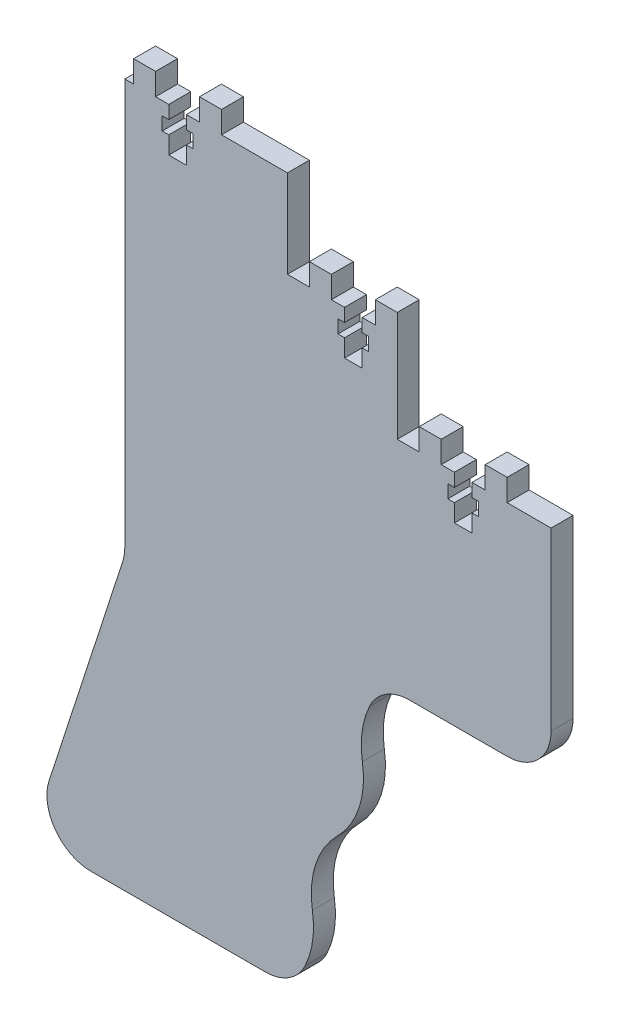
SolidWorks part; units mm, degrees
ref_plane "Plan de face" through (0, 0, 0) normal (0, 0, 1) x (1, 0, 0)
ref_plane "Plan de dessus" through (0, 0, 0) normal (0, 1, 0) x (1, 0, 0)
ref_plane "Plan de droite" through (0, 0, 0) normal (1, 0, 0) x (0, 0, -1)
sketch "Esquisse1" plane through (0, 0, 0) normal (0, 0, 1) x (1, 0, 0)
  line L0 (10, 0) -> (10, -20)
  line L1 (10, -20) -> (15, -20)
  line L2 (35, -20) -> (45, -20)
  line L3 (45, -20) -> (45, -70)
  line L4 (45, -70) -> (7.7444, -70)
  line L5 (7.7444, -70) -> (-15, -140) construction
  line L6 (-15, -140) -> (-73.4888, -140)
  line L7 (-73.4888, -140) -> (-28, 0) construction
  line L8 (-28, 0) -> (-10, 0) construction
  line L9 (-10, 0) -> (-15, 0)
  line L10 (-30, 20) -> (-15, 20)
  line L11 (-50, 20) -> (-52, 20)
  line L12 (-52, 20) -> (-52, -73.8644)
  line L13 (-52, -73.8644) -> (-73.4888, -140)
  line L14 (-15, 20) -> (-15, 0)
  arc A0 (7.7444, -70) -> (2.0583, -87.5) centre (22.0162, -84.311) ccw
  arc A1 (2.0583, -87.5) -> (-3.6278, -105) centre (-17.8996, -90.689) cw
  arc A2 (-3.6278, -105) -> (-9.3139, -122.5) centre (10.644, -119.311) ccw
  arc A3 (-9.3139, -122.5) -> (-15, -140) centre (-29.2718, -125.689) cw
  line B0 (28.5, -23) -> (28.5, -26)
  line B1 (23, -26) -> (23, -30)
  line B2 (27, -30) -> (27, -26)
  line B3 (28.5, -26) -> (27, -26)
  line B4 (25, -20) -> (25, -31.2208) construction
  line B5 (27, -20) -> (30, -20)
  line B6 (30, -15) -> (35, -15)
  line B7 (35, -15) -> (35, -20)
  line B8 (30, -15) -> (30, -20)
  line B9 (23, -20) -> (20, -20)
  line B10 (20, -20) -> (20, -15)
  line B11 (20, -15) -> (15, -15)
  line B12 (15, -15) -> (15, -20)
  line B13 (27, -20) -> (23, -20) construction
  line B14 (23, -20) -> (23, -23)
  line B15 (23, -26) -> (21.5, -26)
  line B16 (21.5, -23) -> (23, -23)
  line B17 (23, -30) -> (27, -30)
  line B18 (27, -23) -> (28.5, -23)
  line B19 (21.5, -26) -> (21.5, -23)
  line B20 (27, -23) -> (27, -20)
  line B21 (25, -30) -> (25, -20) construction
  line B22 (3.5, -3) -> (3.5, -6)
  line B23 (-2, -6) -> (-2, -10)
  line B24 (2, -10) -> (2, -6)
  line B25 (3.5, -6) -> (2, -6)
  line B26 (0, 0) -> (0, -11.2208) construction
  line B27 (2, 0) -> (5, 0)
  line B28 (5, 5) -> (10, 5)
  line B29 (10, 5) -> (10, 0)
  line B30 (5, 5) -> (5, 0)
  line B31 (-2, 0) -> (-5, 0)
  line B32 (-5, 0) -> (-5, 5)
  line B33 (-5, 5) -> (-10, 5)
  line B34 (-10, 5) -> (-10, 0)
  line B35 (2, 0) -> (-2, 0) construction
  line B36 (-2, 0) -> (-2, -3)
  line B37 (-2, -6) -> (-3.5, -6)
  line B38 (-3.5, -3) -> (-2, -3)
  line B39 (-2, -10) -> (2, -10)
  line B40 (2, -3) -> (3.5, -3)
  line B41 (-3.5, -6) -> (-3.5, -3)
  line B42 (2, -3) -> (2, 0)
  line B43 (0, -10) -> (0, 0) construction
  line B44 (-36.5, 17) -> (-36.5, 14)
  line B45 (-42, 14) -> (-42, 10)
  line B46 (-38, 10) -> (-38, 14)
  line B47 (-36.5, 14) -> (-38, 14)
  line B48 (-40, 20) -> (-40, 8.7792) construction
  line B49 (-38, 20) -> (-35, 20)
  line B50 (-35, 25) -> (-30, 25)
  line B51 (-30, 25) -> (-30, 20)
  line B52 (-35, 25) -> (-35, 20)
  line B53 (-42, 20) -> (-45, 20)
  line B54 (-45, 20) -> (-45, 25)
  line B55 (-45, 25) -> (-50, 25)
  line B56 (-50, 25) -> (-50, 20)
  line B57 (-38, 20) -> (-42, 20) construction
  line B58 (-42, 20) -> (-42, 17)
  line B59 (-42, 14) -> (-43.5, 14)
  line B60 (-43.5, 17) -> (-42, 17)
  line B61 (-42, 10) -> (-38, 10)
  line B62 (-38, 17) -> (-36.5, 17)
  line B63 (-43.5, 14) -> (-43.5, 17)
  line B64 (-38, 17) -> (-38, 20)
  line B65 (-40, 10) -> (-40, 20) construction
  dimension "D9" = 40
  dimension "D1" = 25
  dimension "D2" = 20
  dimension "D3" = 120
  dimension "D4" = 40
  dimension "D5" = 50
  dimension "D6" = 45
  dimension "D7" = 18
  dimension "D8" = 72
  dimension "D10" = 20
  dimension "D11" = 97
  dimension "D12" = 5
sketch_block_instance "Insert M4 plots ep 5mm-1"
sketch_block "Insert M4 plots ep 5mm" parameters "D1"=10, "D2"=5, "D3"=5, "D4"=7, "D5"=4, "D6"=3, "D7"=3, "D8"=10
sketch_block_instance "Insert M4 plots ep 5mm-3"
sketch_block_instance "Insert M4 plots ep 5mm-4"
extrude "Boss.-Extru.1" add sketch "Esquisse1" along normal blind 5 contours B42 B40 B22 B25 B24 B39 B23 B37 B41 B38 B36 B31 B32 B33 B34 L8 L7 L6 L5 L4 L3 L2 B7 B6 B8 B5 B20 B18 B0 B3 B2 B17 B1 B15 B19 B16 B14 B9 B10 B11 B12 L1 L0 B29 B28 B30 B27 | A1 L5 | A3 L5
fillet "Congé1" radius 10 5 edges at (-15, -140, 2.5) (7.7444, -70, 2.5) (45, -70, 2.5) (-52, -73.8644, 2.5) (-73.4888, -140, 2.5)
